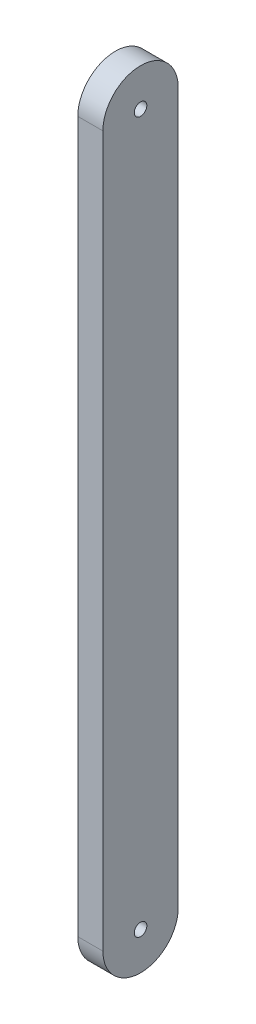
SolidWorks part; units mm, degrees
ref_plane "前视基准面" through (0, 0, 0) normal (0, 0, 1) x (1, 0, 0)
ref_plane "上视基准面" through (0, 0, 0) normal (0, 1, 0) x (1, 0, 0)
ref_plane "右视基准面" through (0, 0, 0) normal (1, 0, 0) x (0, 0, -1)
sketch "草图2" plane through (0, 0, 0) normal (1, 0, 0) x (0, 0, -1)
  line L0 (0, 0) -> (0, 282.909)
  line L2 (30, 282.909) -> (30, 0)
  line L4 (0, 141.4545) -> (392.7465, 141.4545) construction
  arc A0 (0, 282.909) -> (30, 282.909) centre (15, 282.909) cw
  arc A1 (0, 0) -> (30, 0) centre (15, 0) ccw
  dimension "D2" = 15
  dimension "D1" = 282.909
extrude "凸台-拉伸1" add sketch "草图2" along normal blind 10
sketch "草图3" plane through (0, 0, 0) normal (-1, 0, 0) x (0, 0, 1)
  line L0 (-30, 141.4545) -> (131.8765, 141.4545) construction
  line L1 (-30, 0) -> (-30, 282.909) construction
  line L3 (-30, 0) -> (34.9672, 0) construction
  arc A0 (-30, 0) -> (0, 0) centre (-15, 0) ccw construction
  circle A1 centre (-15, 0) radius 2.5
  circle A2 centre (-15, 282.909) radius 2.5
  dimension "D1" = 5
extrude "切除-拉伸1" cut sketch "草图3" against normal blind 10
